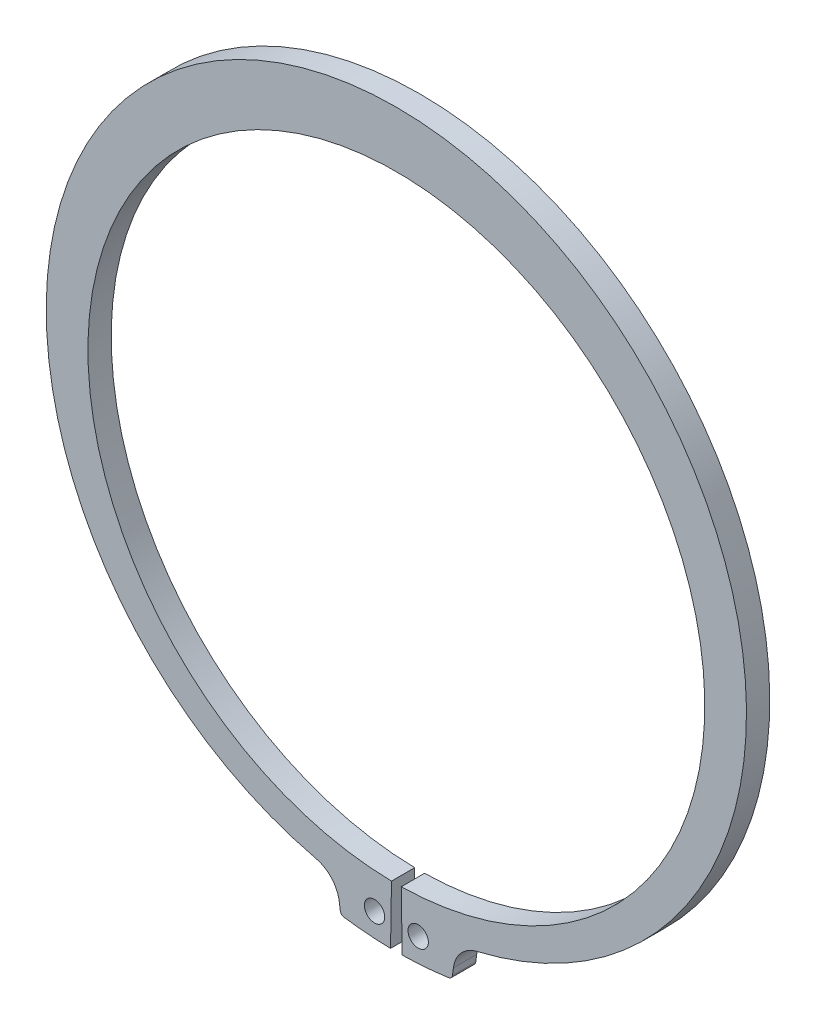
SolidWorks part; units mm, degrees
ref_plane "Plane1" through (0, 0, 0) normal (0, 0, 1) x (1, 0, 0)
ref_plane "Plane2" through (0, 0, 0) normal (0, 1, 0) x (1, 0, 0)
ref_plane "Plane3" through (0, 0, 0) normal (1, 0, 0) x (0, 0, -1)
sketch "Clipboard" plane through (0, 0, 0) normal (0, 0, 1) x (1, 0, 0)
  line L0 (0, 0) -> (9.6, 0)
  line L1 (0, 0) -> (0, 4.8)
  line L2 (0, 0) -> (0, -10.1)
  circle A0 centre (0, 0) radius 1.75
  circle A1 centre (0, 0) radius 55
  dimension "HoleDia" = 3.5
  dimension "ShaftDia" = 110
  dimension "LargeSection" = 9.6
  dimension "SmallSection" = 4.8
  dimension "LugSection" = 10.1
sketch "BodySke" plane through (0, 0, 0) normal (0, 0, 1) x (1, 0, 0)
  line L0 (-1.5431, 0) -> (1.5431, 0) construction
  line L1 (0, 0) -> (0, 62.6) construction
  line L2 (0.8399, -52.9933) -> (1, -63.0921)
  line L3 (-0.8399, -52.9933) -> (-1, -63.0921)
  line L4 (0, 0) -> (15.0536, -61.2781) construction
  line L5 (0, 0) -> (-15.0536, -61.2781) construction
  line L7 (9.7991, -60.5863) -> (9.638, -61.8102)
  line L8 (-9.7991, -60.5863) -> (-9.638, -61.8102)
  circle A0 centre (0, 0) radius 53 construction
  arc A1 (0.8399, -52.9933) -> (-0.8399, -52.9933) centre (0, 0) ccw
  arc A2 (13.7892, -56.1311) -> (-13.7892, -56.1311) centre (0, 2.4337) ccw construction
  arc A3 (1, -63.0921) -> (9.0014, -62.4547) centre (0, 0) ccw
  arc A4 (13.8349, -56.1203) -> (9.7991, -60.5863) centre (15.0536, -61.2781) ccw
  arc A5 (-9.7991, -60.5863) -> (-13.8349, -56.1203) centre (-15.0536, -61.2781) ccw
  arc A6 (-9.0014, -62.4547) -> (-1, -63.0921) centre (0, 0) ccw
  arc A7 (13.8349, -56.1203) -> (-13.8349, -56.1203) centre (0, 2.4337) ccw
  arc A8 (-10.1163, -58.177) -> (10.1163, -58.177) centre (0, 0) ccw construction
  circle A9 centre (3.75, -58.9308) radius 1.75
  circle A10 centre (-3.75, -58.9308) radius 1.75
  arc A11 (9.638, -61.8102) -> (9.0014, -62.4547) centre (8.8944, -61.7123) cw
  arc A12 (-9.638, -61.8102) -> (-9.0014, -62.4547) centre (-8.8944, -61.7123) ccw
  point P28 (9.5642, -62.371)
  point P31 (-9.5642, -62.371)
  dimension "HoleDia" = 3.5
  dimension "GrooveDia" = 106
  dimension "LugRad" = 63.1
  dimension "HoleOffsetRad" = 59.05
  dimension "D3" = 0.75
  dimension "LargeRad" = 62.6
  dimension "SmallRad" = 57.8
  dimension "SmallAngle" = 27.604
  dimension "D2" = 15
  dimension "HoleSpacing" = 7.5
  dimension "Gap" = 2
extrude "Body" add sketch "BodySke" against normal blind 4
sketch "NotSke" plane through (0, 0, 0) normal (0, 0, 1) x (1, 0, 0)
  line L0 (3.75, -57.1808) -> (3.75, -60.6808)
  line L1 (3.75, -60.6808) -> (-3.75, -60.6808)
  line L2 (-3.75, -60.6808) -> (-3.75, -57.1808)
  line L3 (-3.75, -57.1808) -> (3.75, -57.1808)
  circle A0 centre (3.75, -58.9308) radius 1.75 construction
  circle A1 centre (-3.75, -58.9308) radius 1.75 construction
extrude "Notch" [suppressed] cut sketch "NotSke" against normal through all
sketch "UnlSke" plane through (0, 0, 0) normal (0, 0, 1) x (1, 0, 0)
  line L0 (-5.8717, -62.8262) -> (-4.9318, -52.77)
  line L1 (5.8717, -62.8262) -> (4.9318, -52.77)
  arc A0 (4.9318, -52.77) -> (-4.9318, -52.77) centre (0, 0) ccw
  arc A1 (5.8717, -62.8262) -> (-5.8717, -62.8262) centre (0, 0) ccw
  arc A2 (1, -63.0921) -> (9.0014, -62.4547) centre (0, 0) ccw construction
  arc A3 (0.8399, -52.9933) -> (-0.8399, -52.9933) centre (0, 0) ccw construction
  circle A4 centre (-3.75, -58.9308) radius 1.75 construction
  circle A5 centre (3.75, -58.9308) radius 1.75 construction
extrude "Unlug" [suppressed] add sketch "UnlSke" against normal through all
equation "' \"ShaftDia@Clipboard\" = 3"
equation "' \"Thickness@Body\" = 0.4"
equation "' \"GrooveDia@BodySke\" = 2.8"
equation "' \"LugSection@Clipboard\" = 1.9"
equation "' \"LargeSection@Clipboard\" = 0.8"
equation "' \"HoleDia@Clipboard\" = 1.0"
equation "' \"ShaftDia@Clipboard\" = 10"
equation "' \"Thickness@Body\" = 1.0"
equation "' \"GrooveDia@BodySke\" = 9.6"
equation "' \"LugSection@Clipboard\" = 3.3"
equation "' \"LargeSection@Clipboard\" = 1.8"
equation "' \"HoleDia@Clipboard\" = 1.5"
equation "\"SmallSection@Clipboard\" = \"LargeSection@Clipboard\" * 0.5"
equation "\"Gap@BodySke\" =  \"Thickness@Body\" / 2"
equation "\"LargeRad@BodySke\" =  \"GrooveDia@BodySke\" / 2 +  \"LargeSection@Clipboard\""
equation "\"SmallRad@BodySke\" =  \"GrooveDia@BodySke\" / 2 +  \"SmallSection@Clipboard\""
equation "\"LugRad@BodySke\" = \"GrooveDia@BodySke\" / 2 + \"LugSection@Clipboard\""
equation "\"HoleOffsetRad@BodySke\" = (  \"ShaftDia@Clipboard\" / 2 + \"LugRad@BodySke\" ) / 2"
equation "\"HoleSpacing@BodySke\" = \"Gap@BodySke\"  * 2 +  \"HoleDia@Clipboard\""
equation "\"HoleDia@BodySke\" =  \"HoleDia@Clipboard\""
equation "\"SmallAngle@BodySke\" = atn(\"HoleSpacing@BodySke\" / 2 / sqr(\"HoleOffsetRad@BodySke\"  * \"HoleOffsetRad@BodySke\" - (\"HoleSpacing@BodySke\" / 2) * (\"HoleSpacing@BodySke\" / 2) ))  * 7 *  (\"LargeRad@BodySke\" / \"SmallRad@BodySke\")* ( 180 / 3.141593)"
